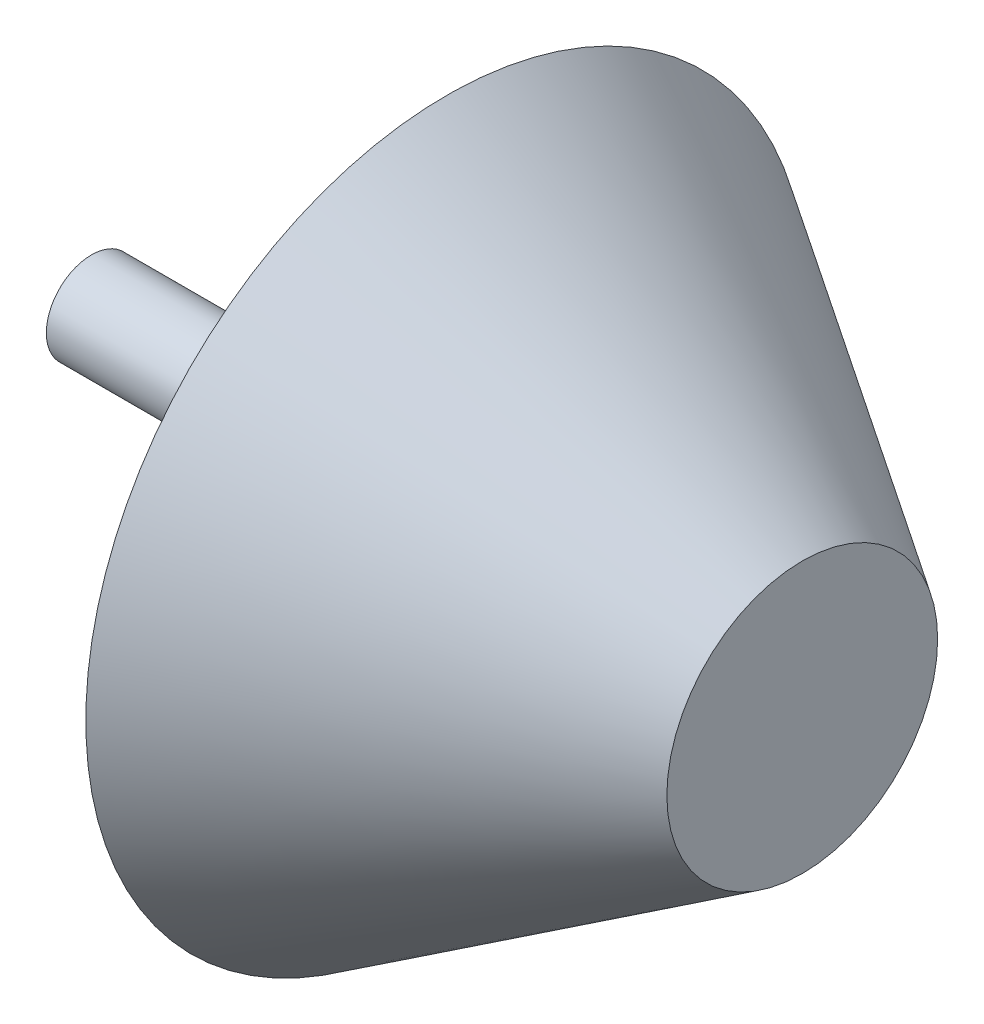
SolidWorks part; units mm, degrees
ref_plane "Front Plane" through (0, 0, 0) normal (1, 0, 0) x (0, 1, 0)
ref_plane "Top Plane" through (0, 0, 0) normal (0, 0, 1) x (0, 1, 0)
ref_plane "Right Plane" through (0, 0, 0) normal (0, 1, 0) x (-1, 0, 0)
sketch "Sketch2" plane through (0, 0, 0) normal (1, 0, 0) x (0, 1, 0)
  circle A0 centre (0, 0) radius 101.6
  dimension "D1" = 203.2
ref_plane "Plane1" through (100, 0, 0) normal (1, 0, 0) x (0, 1, 0)
sketch "Sketch3" plane through (100, 0, 0) normal (1, 0, 0) x (0, 1, 0)
  circle A0 centre (0, 0) radius 38.1
  dimension "D1" = 76.2
loft "Loft1" add profiles "Sketch2", "Sketch3"
sketch "Sketch4" plane through (0, 0, 0) normal (-1, 0, 0) x (0, -1, 0)
  circle A0 centre (0, 0) radius 12.7
  dimension "D1" = 25.4
extrude "Boss-Extrude1" add sketch "Sketch4" along normal blind 100
